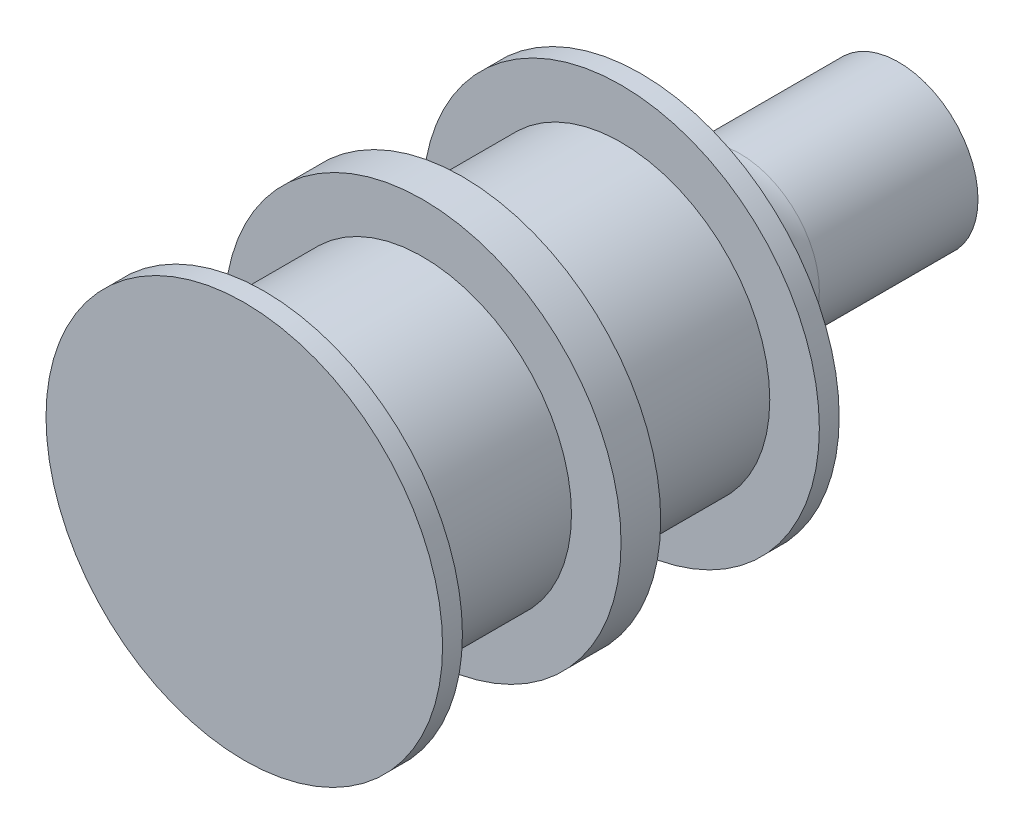
SolidWorks part; units mm, degrees
ref_plane "Alzado" through (0, 0, 0) normal (1, 0, 0) x (0, 1, 0)
ref_plane "Planta" through (0, 0, 0) normal (0, 0, 1) x (0, 1, 0)
ref_plane "Vista lateral" through (0, 0, 0) normal (0, 1, 0) x (-1, 0, 0)
sketch "Croquis1" plane through (0, 0, 0) normal (0, 0, 1) x (0, 1, 0)
  circle A0 centre (0, 0) radius 10
  dimension "D1" = 20
extrude "Saliente-Extruir1" add sketch "Croquis1" along normal mid plane 10
sketch "Croquis2" plane through (0, 0, 0) normal (0, 0, 1) x (0, 1, 0)
  circle A0 centre (0, 0) radius 10
  circle A1 centre (0, 0) radius 7.5
  dimension "D1" = 15
extrude "Cortar-Extruir1" cut sketch "Croquis2" against normal mid plane 8
mirror "Simetría2" about plane through (0, 0, 5) normal (0, 0, 1) of bodies 102
sketch "Croquis3" plane through (0, 0, -5) normal (0, 0, -1) x (-1, 0, 0)
  circle A0 centre (0, 0) radius 4
  dimension "D1" = 8
extrude "Saliente-Extruir2" add sketch "Croquis3" along normal blind 13
sketch "Croquis4" plane through (0, 0, -18) normal (0, 0, -1) x (-1, 0, 0)
  circle A0 centre (0, 0) radius 2.5
  dimension "D1" = 5
extrude "Cortar-Extruir2" cut sketch "Croquis4" against normal blind 8
fillet "Redondeo1" radius 5 1 edges at (-4, 0, -5)
